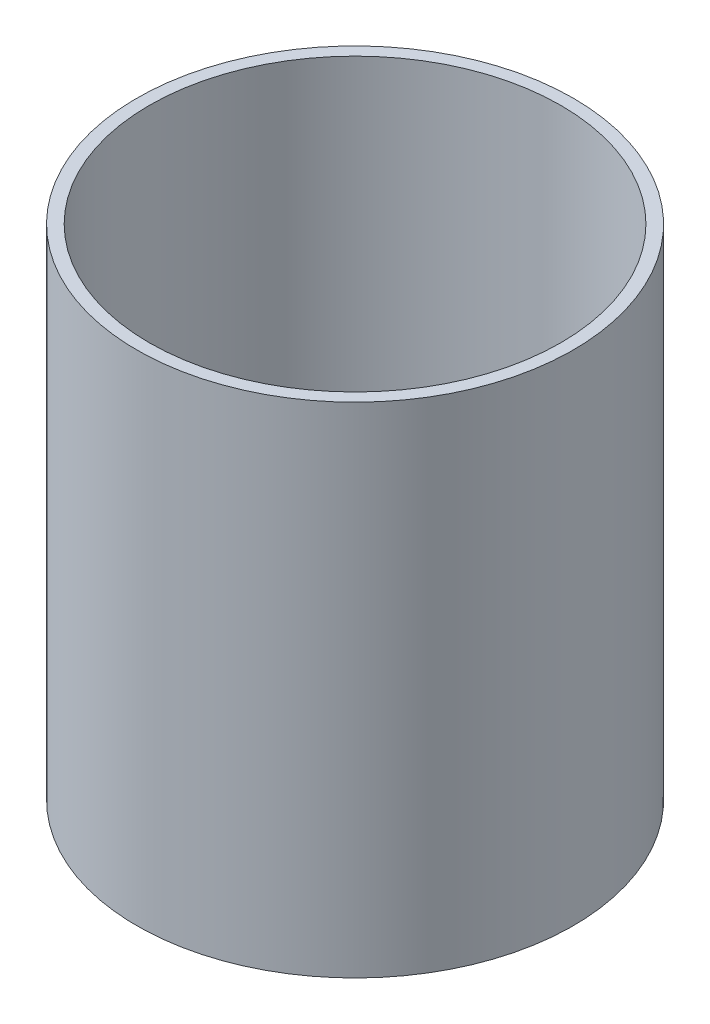
SolidWorks part; units mm, degrees
ref_plane "Alzado" through (0, 0, 0) normal (0, 0, 1) x (1, 0, 0)
ref_plane "Planta" through (0, 0, 0) normal (0, 1, 0) x (1, 0, 0)
ref_plane "Vista lateral" through (0, 0, 0) normal (1, 0, 0) x (0, 0, -1)
sketch "Croquis1" plane through (0, 0, 0) normal (1, 0, 0) x (0, 0, -1)
  line L0 (0, -209.1231) -> (-165, -209.1231)
  line L1 (-165, -209.1231) -> (-165, 180.8769)
  line L2 (-165, 180.8769) -> (-175, 180.8769)
  line L3 (-175, 180.8769) -> (-175, -219.1231)
  line L4 (-175, -219.1231) -> (0, -219.1231)
  line L5 (0, -219.1231) -> (0, 267.2657) construction
  line L6 (0, -209.1231) -> (0, -219.1231)
  dimension "D1" = 175
  dimension "D2" = 400
  dimension "D3" = 10
  dimension "D4" = 10
revolve "Revolución1" add sketch "Croquis1" angle 360 about L5
